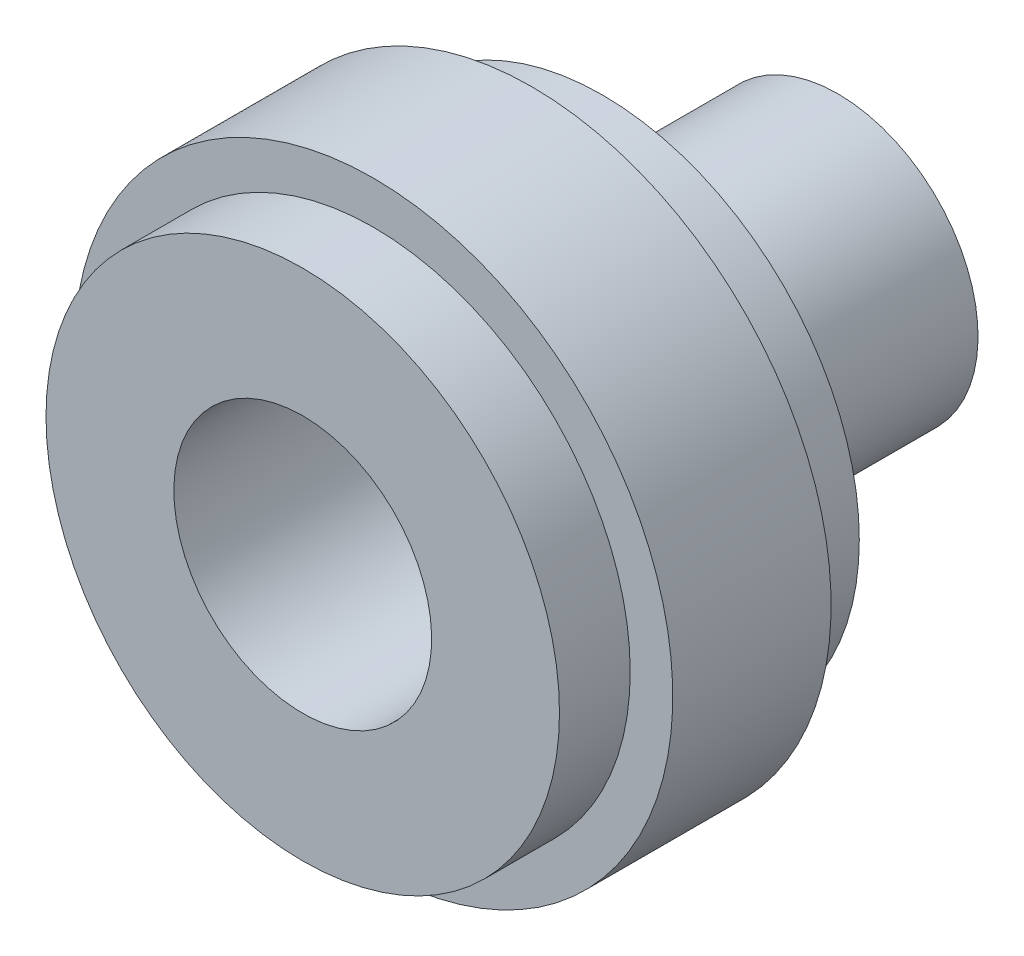
SolidWorks part; units mm, degrees
ref_plane "Front Plane" through (0, 0, 0) normal (0, 0, 1) x (1, 0, 0)
ref_plane "Top Plane" through (0, 0, 0) normal (0, 1, 0) x (1, 0, 0)
ref_plane "Right Plane" through (0, 0, 0) normal (1, 0, 0) x (0, 0, -1)
sketch "Sketch2" plane through (0, 0, 0) normal (1, 0, 0) x (0, 0, -1)
  line L0 (0, 0) -> (-6.9967, 0) construction
  line L1 (0, 0) -> (0, 9.8665) construction
  line L2 (-5.4356, 4.6736) -> (1.1938, 4.6736)
  line L3 (1.1938, 4.6736) -> (1.1938, 1.7526)
  line L4 (1.1938, 1.7526) -> (13.97, 1.7526)
  line L5 (13.97, 1.7526) -> (13.97, 5.08)
  line L6 (13.97, 5.08) -> (5.4356, 5.08)
  line L7 (5.4356, 5.08) -> (5.4356, 9.3091)
  line L8 (5.4356, 9.3091) -> (2.8702, 9.3091)
  line L9 (2.8702, 9.3091) -> (2.8702, 10.8521)
  line L10 (2.8702, 10.8521) -> (-2.8702, 10.8521)
  line L11 (-2.8702, 10.8521) -> (-2.8702, 9.3091)
  line L12 (-2.8702, 9.3091) -> (-5.4356, 9.3091)
  line L13 (-5.4356, 9.3091) -> (-5.4356, 4.6736)
  point P6 (0, 0)
  dimension "D1" = 9.3472
  dimension "D2" = 3.5052
  dimension "D3" = 6.6294
  dimension "D4" = 18.6182
  dimension "D5" = 5.7404
  dimension "D6" = 10.8712
  dimension "D7" = 21.7043
  dimension "D8" = 10.16
  dimension "D9" = 19.4056
revolve "Revolve1" add sketch "Sketch2" angle 360 about L0
